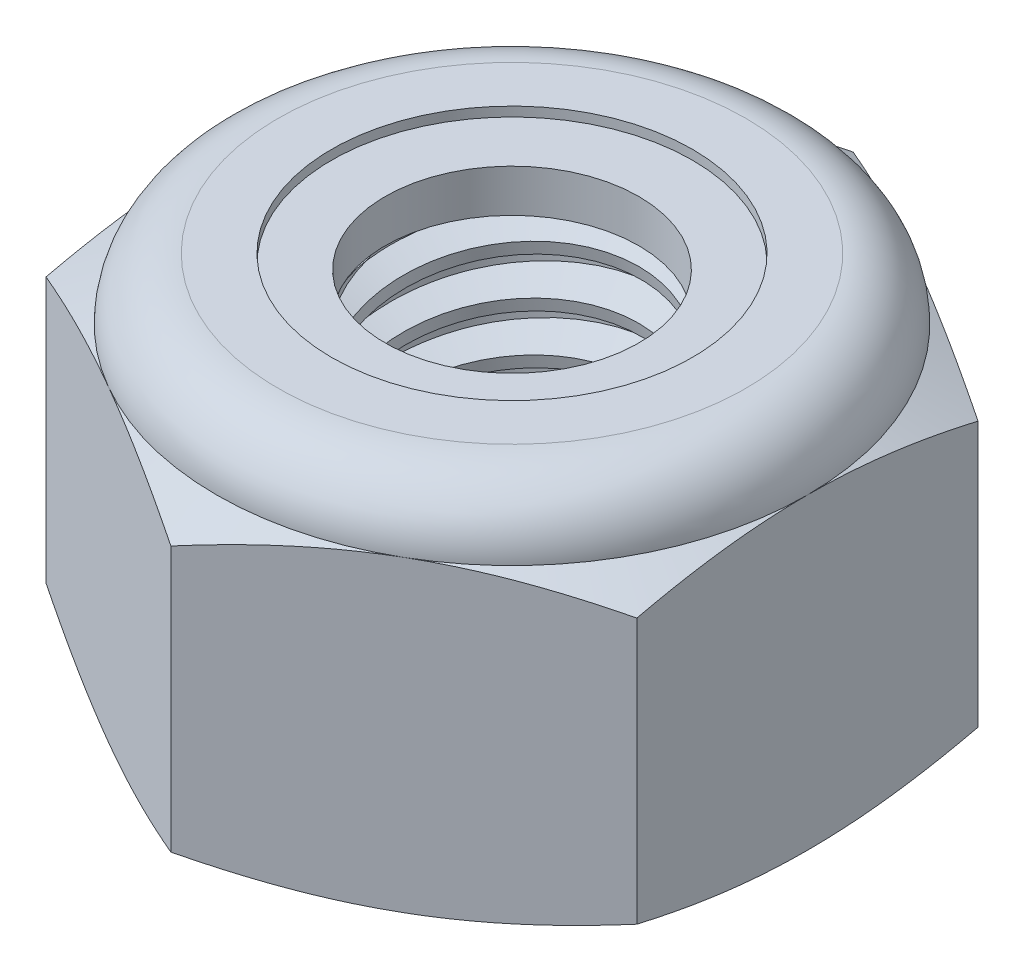
SolidWorks part; units mm, degrees
ref_plane "Front" through (0, 0, 0) normal (0, 0, 1) x (1, 0, 0)
ref_plane "Top" through (0, 0, 0) normal (0, 1, 0) x (1, 0, 0)
ref_plane "Right" through (0, 0, 0) normal (1, 0, 0) x (0, 0, -1)
sketch "Sketch1" plane through (0, 0, 0) normal (0, 1, 0) x (1, 0, 0)
  line L1 (0, 5.4993) -> (-4.7625, 2.7496)
  line L2 (-4.7625, 2.7496) -> (-4.7625, -2.7496)
  line L3 (-4.7625, -2.7496) -> (0, -5.4993)
  line L4 (0, -5.4993) -> (4.7625, -2.7496)
  line L5 (4.7625, -2.7496) -> (4.7625, 2.7496)
  line L6 (4.7625, 2.7496) -> (0, 5.4993)
  circle A0 centre (0, 0) radius 4.7625 construction
  dimension "Hex Flats" = 9.525
extrude "Extrude1" add sketch "Sketch1" along normal blind 5.9531
sketch "Sketch2" plane through (0, 0, 0) normal (1, 0, 0) x (0, 0, -1)
  line L0 (-2.413, 0) -> (-2.413, 5.9531) construction
  line L1 (0, 0) -> (2.413, 0)
  line L2 (0, 0) -> (0, 5.9531)
  line L3 (0, 5.9531) -> (2.413, 5.9531)
  line L4 (2.413, 0) -> (2.413, 5.9531)
  line L5 (-2.7496, 5.9531) -> (2.7496, 5.9531) construction
  line L7 (0, -2.413) -> (0, 0) construction
  dimension "Thread Dia" = 4.826
revolve "Revolve1" add sketch "Sketch2" angle 360 about L7
sketch "Sketch3" plane through (0, 0, 0) normal (1, 0, 0) x (0, 0, -1)
  line L0 (2.413, 5.9531) -> (-2.413, 5.9531) construction
  line L1 (-2.413, 5.9531) -> (-2.413, 5.1594) construction
  line L2 (-2.413, 5.1594) -> (2.413, 5.9531) construction
  line L3 (2.413, 5.9531) -> (2.4291, 5.8552) construction
  line L4 (2.4291, 5.8552) -> (2.5418, 5.1699)
  line L5 (2.5418, 5.1699) -> (2.0776, 5.3449)
  line L6 (2.0776, 5.3449) -> (2.0454, 5.5407)
  line L7 (2.0454, 5.5407) -> (2.4291, 5.8552)
  line L8 (2.0615, 5.4428) -> (2.4855, 5.5126) construction
  line L9 (2.413, 5.9531) -> (2.413, 5.5006) construction
  line L10 (2.413, 5.5006) -> (-2.413, 4.7069) construction
  line L11 (-2.413, 4.7069) -> (-2.413, 5.1594) construction
  line L12 (-0.1397, 5.9531) -> (0.1397, 4.2544) construction
  line L13 (-2.413, 0) -> (-2.413, 5.9531) construction
  line L14 (0, 5.9531) -> (2.413, 5.9531) construction
  line L15 (2.413, 0) -> (2.413, 5.9531) construction
  point P13 (0, 5.1038)
  dimension "D1" = 0.0992
  dimension "D2" = 0.1984
  dimension "Thread Pitch" = 0.7937
  dimension "D4" = 60
  dimension "D5" = 0.7937
revolve "Cut-Revolve1" cut sketch "Sketch3" angle 360 about L12
pattern_linear "LPattern1" count 8 spacing 0.7937 along (0, -1, 0) count 2 spacing 0.7937 along (0, 1, 0) of "Cut-Revolve1"
sketch "Sketch4" plane through (0, 0, 0) normal (1, 0, 0) x (0, 0, -1)
  line L0 (0, 5.9531) -> (2.413, 5.9531)
  line L1 (2.413, 5.9531) -> (2.0454, 5.7817)
  line L2 (2.0454, 5.7817) -> (2.0454, 0.1714)
  line L3 (2.0454, 0.1714) -> (2.413, 0)
  line L4 (2.413, 0) -> (0, 0)
  line L5 (0, 0) -> (0, 5.9531)
  line L6 (2.413, 0) -> (2.413, 5.9531) construction
  line L7 (0, 5.9531) -> (2.413, 5.9531) construction
  line L8 (0, 0) -> (2.413, 0) construction
  line L9 (0, 0) -> (0, 5.9531) construction
  line L10 (0, 5.9531) -> (0, 6.3587) construction
  dimension "D1" = 25
revolve "Cut-Revolve2" cut sketch "Sketch4" angle 360 about L10
combine bodies "Combine1" operation type subtract main body 112 bodies to subtract 111
sketch "Sketch5" plane through (0, 0, 0) normal (1, 0, 0) x (0, 0, -1)
  line L0 (0, 0) -> (4.7625, 0)
  line L1 (4.7625, 0) -> (5.4993, 0.3436)
  line L2 (5.4993, 0.3436) -> (5.4993, 4.6174)
  line L3 (5.4993, 4.6174) -> (4.7625, 4.9609)
  line L4 (3.7703, 5.9531) -> (3.7703, 7.2231)
  line L5 (3.7703, 7.2231) -> (6.7693, 7.2231)
  line L6 (6.7693, 7.2231) -> (6.7693, -1.27)
  line L7 (6.7693, -1.27) -> (0, -1.27)
  line L8 (0, -1.27) -> (0, 0)
  line L9 (4.7625, 4.9609) -> (4.7625, 0) construction
  line L10 (0, 0) -> (2.413, 0) construction
  line L13 (5.4993, 2.4805) -> (6.7693, 2.4805) construction
  line L14 (5.4993, 5.9531) -> (5.4993, 0) construction
  line L15 (0, 0) -> (0, 7.2231) construction
  line L20 (0, 7.2231) -> (3.7703, 7.2231) construction
  line L22 (0, 5.9531) -> (2.413, 5.9531) construction
  arc A0 (4.7625, 4.9609) -> (3.7703, 5.9531) centre (3.7703, 4.9609) ccw
  dimension "D1" = 25
  dimension "D2" = 1.27
  dimension "D3" = 5.9531
  dimension "D4" = 0.9922
revolve "Cut-Revolve3" cut sketch "Sketch5" angle 360 about L15
sketch "Sketch6" plane through (0, 0, 0) normal (1, 0, 0) x (0, 0, -1)
  line L0 (0, 4.9609) -> (4.6101, 4.9609)
  line L1 (3.7703, 5.8007) -> (2.9079, 5.8007)
  line L2 (0, 7.2231) -> (0, 4.9609)
  line L3 (2.9079, 7.2231) -> (0, 7.2231)
  line L4 (0, 7.2231) -> (3.7703, 7.2231) construction
  line L5 (0, 0) -> (0, 7.2231) construction
  line L6 (0, 7.2231) -> (0, 44.323) construction
  line L7 (2.9079, 5.8007) -> (2.9079, 7.2231)
  line L8 (3.7703, 5.9531) -> (3.7703, 5.8007) construction
  line L9 (2.9079, 5.8007) -> (2.0454, 5.8007) construction
  line L10 (2.0454, 5.8007) -> (2.0454, 5.7817) construction
  arc A0 (4.6101, 4.9609) -> (3.7703, 5.8007) centre (3.7703, 4.9609) ccw
  arc A1 (4.7625, 4.9609) -> (3.7703, 5.9531) centre (3.7703, 4.9609) ccw construction
  dimension "D1" = 0.1524
revolve "Cut-Revolve4" cut sketch "Sketch6" angle 360 about L6
sketch "Sketch7" plane through (0, 0, 0) normal (1, 0, 0) x (0, 0, -1)
  line L0 (2.0454, 5.0371) -> (4.5301, 5.0371)
  line L1 (3.7703, 5.7245) -> (2.0454, 5.7245)
  line L2 (2.0454, 5.7245) -> (2.0454, 5.0371)
  line L3 (2.0454, 5.0371) -> (0, 5.0371) construction
  line L4 (0, 5.0371) -> (0, 5.7245) construction
  line L5 (0, 5.7245) -> (2.0454, 5.7245) construction
  line L6 (2.0454, 5.0371) -> (2.0454, 4.9609) construction
  line L7 (0, 4.9609) -> (4.6101, 4.9609) construction
  line L8 (3.7703, 5.7245) -> (3.7703, 5.8007) construction
  arc A0 (4.5301, 5.0371) -> (3.7703, 5.7245) centre (3.7703, 4.9609) ccw
  arc A2 (4.6101, 4.9609) -> (3.7703, 5.8007) centre (3.7703, 4.9609) ccw construction
  dimension "D1" = 0.0762
revolve "Revolve2" add sketch "Sketch7" angle 360 about L4
move or copy body "Body-Move/Copy1" [suppressed] bodies to move or copy 115 116
equation "\"D1@Sketch3\"=\"Thread Pitch@Sketch3\"/8"
equation "\"D2@Sketch3\"=\"Thread Pitch@Sketch3\"/4"
equation "\"D5@Sketch3\"=\"Thread Pitch@Sketch3\""
equation "\"D4@LPattern1\"=\"Thread Pitch@Sketch3\""
equation "\"D3@LPattern1\"=\"Thread Pitch@Sketch3\""
equation "\"D1@LPattern1\"=\"Height@Extrude1\"/\"Thread Pitch@Sketch3\""
equation "\"D4@Sketch5\"=\"Height@Extrude1\"/6"
